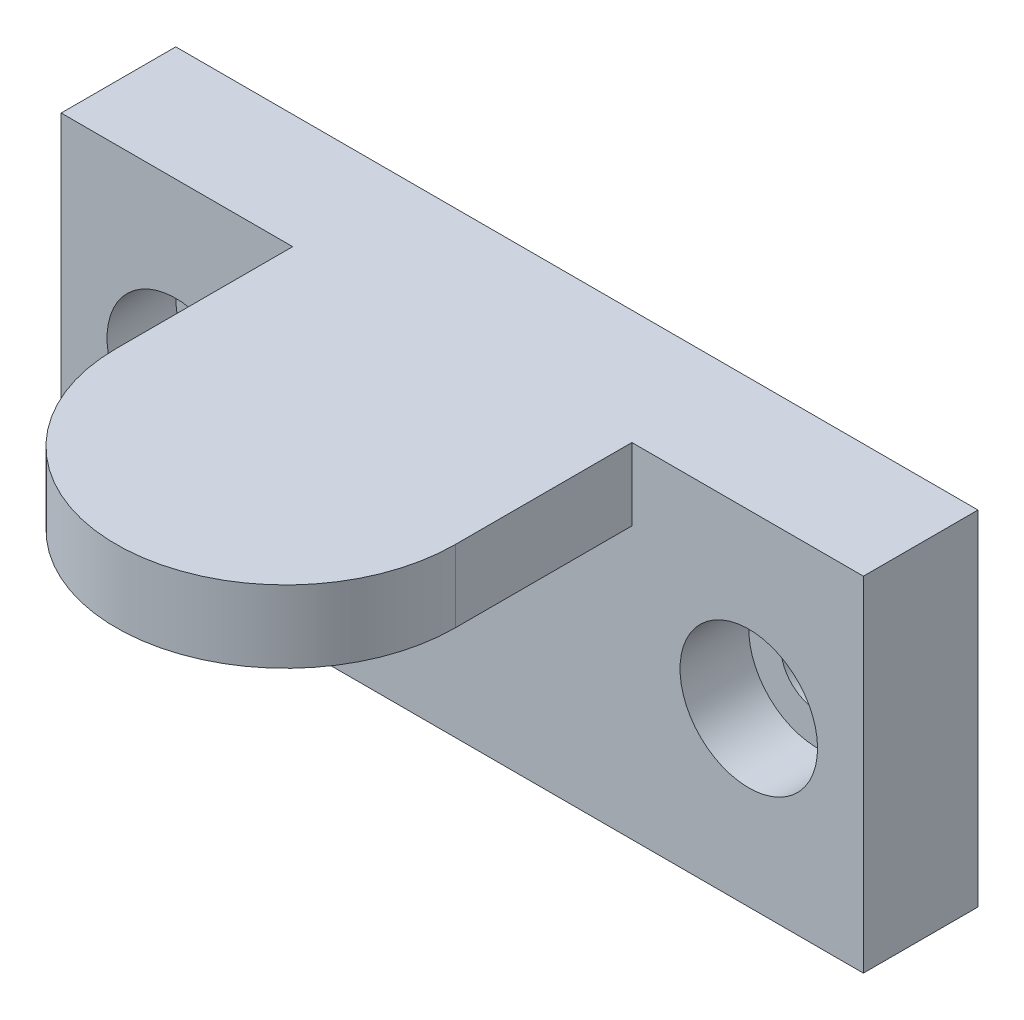
SolidWorks part; units mm, degrees
ref_plane "Front Plane" through (0, 0, 0) normal (0, 0, 1) x (1, 0, 0)
ref_plane "Top Plane" through (0, 0, 0) normal (0, 1, 0) x (1, 0, 0)
ref_plane "Right Plane" through (0, 0, 0) normal (1, 0, 0) x (0, 0, -1)
sketch "Sketch1" plane through (0, 0, 0) normal (0, 0, 1) x (1, 0, 0)
  line L0 (10, 0) -> (10, -30) construction
  line L1 (0, 0) -> (70, 0)
  line L2 (0, 0) -> (0, -30)
  line L3 (0, -30) -> (70, -30)
  line L4 (70, 0) -> (70, -30)
  line L5 (60, 0) -> (60, -30) construction
  dimension "D1" = 70
  dimension "D2" = 30
  dimension "D3" = 10
  dimension "D4" = 10
extrude "Boss-Extrude1" add sketch "Sketch1" along normal blind 10
sketch "Sketch2" plane through (0, 0, 10) normal (0, 0, 1) x (1, 0, 0)
  line L0 (60, 0) -> (60, -30) construction
  line L1 (10, 0) -> (10, -30) construction
  line L2 (60, 0) -> (60, -30)
  line L3 (10, 0) -> (10, -30)
  circle A0 centre (10, -15) radius 6
  circle A1 centre (60, -15) radius 6
  dimension "D1" = 12
  dimension "D2" = 12
extrude "Cut-Extrude1" cut sketch "Sketch2" against normal blind 6 contours A0 | A1
sketch "Sketch3" plane through (0, 0, 4) normal (0, 0, 1) x (1, 0, 0)
  line L0 (10, 0) -> (10, -30) construction
  line L1 (60, 0) -> (60, -30) construction
  circle A0 centre (10, -15) radius 3.2
  circle A1 centre (60, -15) radius 3.2
  dimension "D1" = 6.4
  dimension "D2" = 6.4
extrude "Cut-Extrude2" cut sketch "Sketch3" against normal through all
ref_plane "Plane1" through (0, 0, 0) normal (0, 1, 0) x (1, 0, 0)
sketch "Sketch8" plane through (0, 0, 0) normal (0, 1, 0) x (1, 0, 0)
  line L0 (35, -10) -> (35, -25.4)
  line L1 (70, -10) -> (0, -10) construction
  dimension "D1" = 15.4
sketch "Sketch9" plane through (0, 0, 0) normal (0, 1, 0) x (1, 0, 0)
  line L0 (49.8, -25.4) -> (49.8, -10)
  line L1 (70, -10) -> (0, -10) construction
  line L2 (20.2, -25.4) -> (20.2, -10)
  line L3 (20.2, -10) -> (49.8, -10)
  circle A0 centre (35, -25.4) radius 14.8
  arc A1 (20.2, -25.4) -> (49.8, -25.4) centre (35, -25.4) cw
  dimension "D1" = 29.6
extrude "Boss-Extrude3" add sketch "Sketch9" against normal blind 6.3 contours A0 | A1 L0 L3 L2
sketch "Sketch10" plane through (0, 0, 10) normal (0, 0, 1) x (1, 0, 0)
  line L0 (10, -15) -> (60, -15) construction
  line L1 (10, 0) -> (10, -30) construction
  line L2 (60, 0) -> (60, -30) construction
